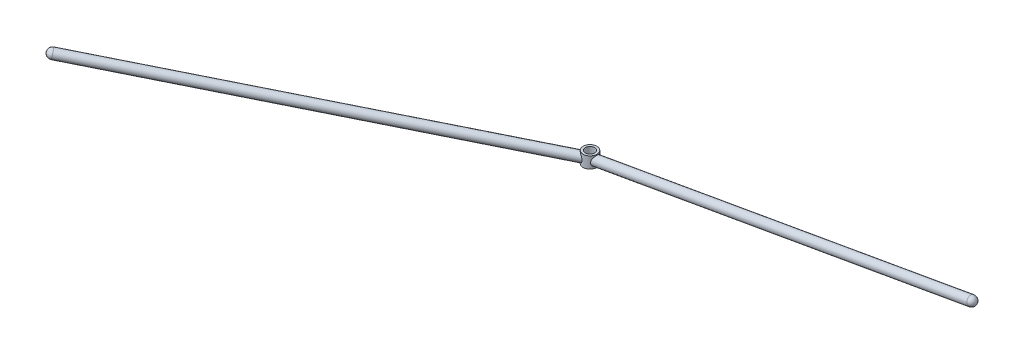
SolidWorks part; units mm, degrees
ref_plane "Plan de face" through (0, 0, 0) normal (0, 0, 1) x (1, 0, 0)
ref_plane "Plan de dessus" through (0, 0, 0) normal (0, 1, 0) x (1, 0, 0)
ref_plane "Plan de droite" through (0, 0, 0) normal (1, 0, 0) x (0, 0, -1)
sketch "Esquisse1" plane through (0, 0, 0) normal (0, 1, 0) x (1, 0, 0)
  arc A0 (0, -3) -> (0, 3) centre (0, 0) ccw
  arc A1 (0, 3) -> (0, -3) centre (0, 0) ccw
  dimension "D1" = 3
extrude "Boss.-Extru.6" add sketch "Esquisse1" along normal blind 5 contours A0 A1
sketch "Esquisse3" plane through (0, 0, 0) normal (1, 0, 0) x (0, 0, -1)
  line L10 (-3, 2.5) -> (3, 2.5)
  line L13 (-3, 5) -> (-3, 0) construction
  line L14 (3, 0) -> (3, 5) construction
ref_plane "Plan1" through (0.4275, 0.0754, 0) normal (0.9848, 0.1736, 0) x (0, 0, -1)
sketch "Esquisse4" plane through (0.4275, 0.0754, 0) normal (0.9848, 0.1736, 0) x (0, 0, -1)
  circle A0 centre (0, 2) radius 2
  ellipse E0 centre (0, 0) end of major axis (3, 0) minor radius 0.5209 (-3, 0) -> (3, 0) ccw construction
  dimension "D1" = 4
  dimension "D2" = 2
extrude "Boss.-Extru.5" add sketch "Esquisse4" along normal blind 170
fillet "Congé3" radius 2 1 edges at (167.1503, 33.5348, 0)
pattern_circular "Répétition circulaire1" count 2 over 140 about axis through (0, 0, 0) along (0, 1, 0) of "Boss.-Extru.5", "Congé3"
sketch "Esquisse6" plane through (0, 5, 0) normal (0, 1, 0) x (1, 0, 0)
  circle A0 centre (0, 0) radius 2
  dimension "D1" = 4
extrude "Enlèv. mat.-Extru.2" cut sketch "Esquisse6" against normal through all
